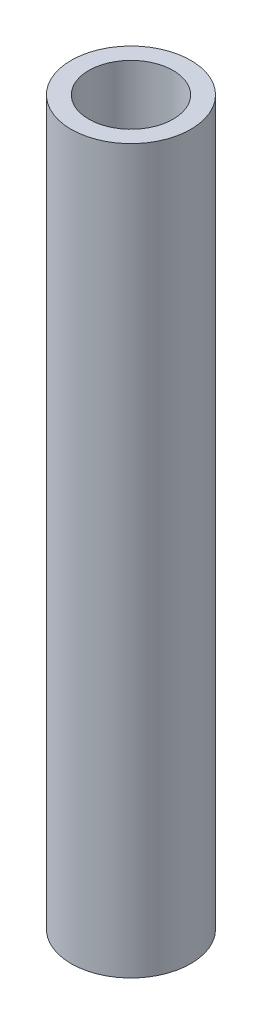
SolidWorks part; units mm, degrees
ref_plane "Alzado" through (0, 0, 0) normal (0, 0, 1) x (1, 0, 0)
ref_plane "Planta" through (0, 0, 0) normal (0, 1, 0) x (1, 0, 0)
ref_plane "Vista lateral" through (0, 0, 0) normal (1, 0, 0) x (0, 0, -1)
sketch "Croquis1" plane through (0, 0, 0) normal (0, 1, 0) x (1, 0, 0)
  circle A0 centre (0, 0) radius 8.5
  circle A1 centre (0, 0) radius 6
  dimension "D1" = 12
  dimension "D2" = 17
extrude "Saliente-Extruir1" add sketch "Croquis1" along normal blind 102.7
